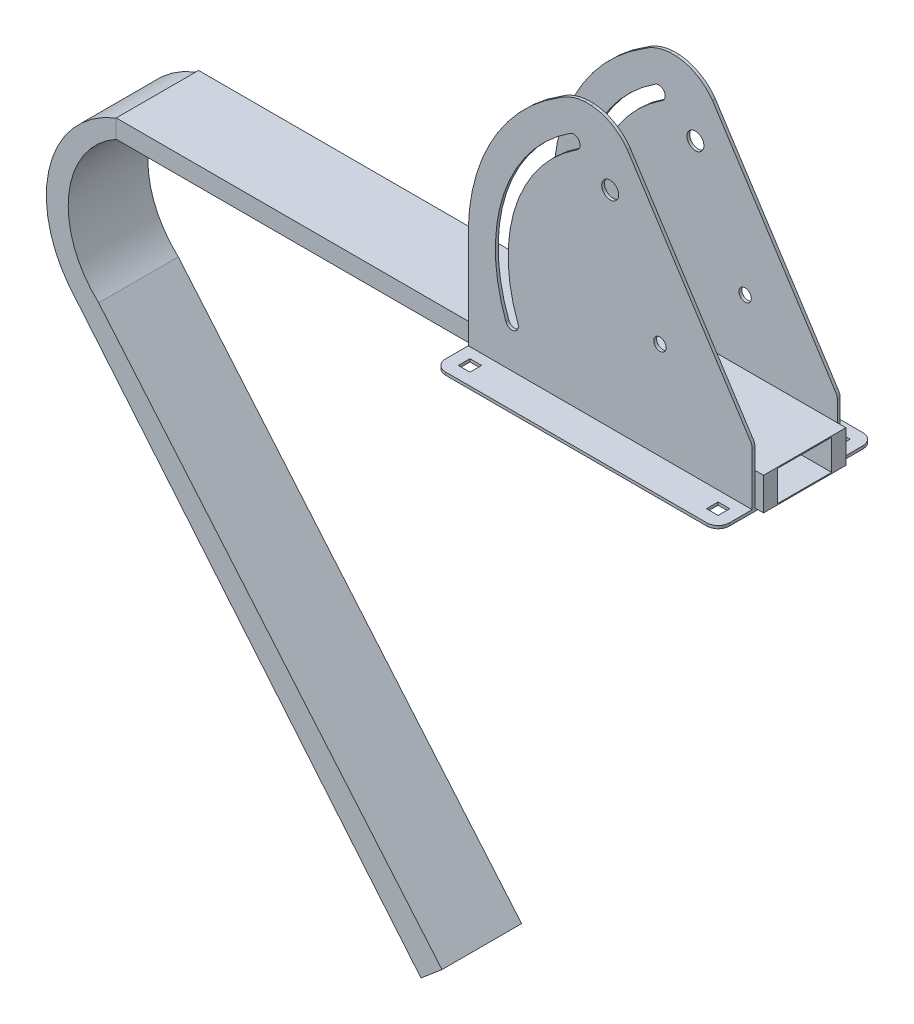
SolidWorks part; units mm, degrees
ref_plane "Alzado" through (0, 0, 0) normal (0, 0, 1) x (1, 0, 0)
ref_plane "Planta" through (0, 0, 0) normal (0, 1, 0) x (1, 0, 0)
ref_plane "Vista lateral" through (0, 0, 0) normal (1, 0, 0) x (0, 0, -1)
sketch "Croquis1" plane through (0, 0, 0) normal (0, 1, 0) x (1, 0, 0)
  line L0 (0, 46.5) -> (0, 38.3) construction
  line L1 (-100, 55) -> (100, 55)
  line L2 (-100, 55) -> (-100, -55)
  line L3 (-100, -55) -> (100, -55)
  line L4 (100, 55) -> (100, -55)
  line L5 (-100, 55) -> (100, -55) construction
  line L6 (-100, -55) -> (100, 55) construction
  line L7 (-91.5, 0) -> (-83.3, 0) construction
  line L8 (91.5, 0) -> (83.3, 0) construction
  line L9 (0, -46.5) -> (0, -38.3) construction
  line L11 (-91.5, 46.5) -> (91.5, 46.5)
  line L12 (-91.5, 46.5) -> (-91.5, -46.5)
  line L13 (-91.5, -46.5) -> (91.5, -46.5)
  line L14 (91.5, 46.5) -> (91.5, -46.5)
  line L15 (-83.3, 38.3) -> (83.3, 38.3)
  line L16 (-83.3, 38.3) -> (-83.3, -38.3)
  line L17 (-83.3, -38.3) -> (83.3, -38.3)
  line L18 (83.3, 38.3) -> (83.3, -38.3)
  line L19 (-91.5, 46.5) -> (-83.3, 46.5)
  line L20 (-91.5, 46.5) -> (-91.5, 38.3)
  line L21 (-91.5, 38.3) -> (-83.3, 38.3)
  line L22 (-83.3, 46.5) -> (-83.3, 38.3)
  line L23 (91.5, 46.5) -> (83.3, 46.5)
  line L24 (91.5, 46.5) -> (91.5, 38.3)
  line L25 (91.5, 38.3) -> (83.3, 38.3)
  line L26 (83.3, 46.5) -> (83.3, 38.3)
  line L27 (91.5, -46.5) -> (83.3, -46.5)
  line L28 (91.5, -46.5) -> (91.5, -38.3)
  line L29 (91.5, -38.3) -> (83.3, -38.3)
  line L30 (83.3, -46.5) -> (83.3, -38.3)
  line L31 (-91.5, -46.5) -> (-83.3, -46.5)
  line L32 (-91.5, -46.5) -> (-91.5, -38.3)
  line L33 (-91.5, -38.3) -> (-83.3, -38.3)
  line L34 (-83.3, -46.5) -> (-83.3, -38.3)
  point P0 (0, 0)
extrude "Saliente-Extruir1" add sketch "Croquis1" along normal blind 2 contours L4 L1 L2 L3 L11 L14 L13 L12 | L26 L11 L22 L15 | L18 L15 L16 L17 | L12 L33 L16 L21 | L34 L13 L30 L17 | L29 L14 L25 L18
sketch "Croquis2" plane through (0, 2, 0) normal (0, 1, 0) x (1, 0, 0)
  line L1 (-92, 55) -> (92, 55)
  line L2 (-100, 47) -> (-100, -47)
  line L3 (-92, -55) -> (92, -55)
  line L4 (100, 47) -> (100, -47)
  line L5 (-100, 55) -> (100, 55)
  line L6 (-100, 55) -> (-100, -55)
  line L7 (-100, -55) -> (100, -55)
  line L8 (100, 55) -> (100, -55)
  arc A0 (92, 55) -> (100, 47) centre (92, 47) cw
  arc A1 (92, -55) -> (100, -47) centre (92, -47) ccw
  arc A2 (-100, -47) -> (-92, -55) centre (-92, -47) ccw
  arc A3 (-92, 55) -> (-100, 47) centre (-92, 47) ccw
  point P10 (100, -55)
  point P15 (-100, 55)
  line M21 (100, -55) -> (100, 55)
  line M22 (100, 55) -> (-100, 55)
  line M23 (-100, 55) -> (-100, -55)
  line M24 (-100, -55) -> (100, -55)
  dimension "D1" = 8
extrude "Cortar-Extruir1" cut sketch "Croquis2" against normal blind 2 contours A3 M22 M23 | A2 M23 M24 | A1 M24 M21 | A0 M22 M21
sketch "Croquis3" plane through (0, 2, 0) normal (0, 1, 0) x (1, 0, 0)
  line L0 (0, 0) -> (0, 31) construction
  line L1 (0, 0) -> (0, -31) construction
  line L2 (0, 31) -> (100, 31) construction
  line L3 (100, 47) -> (100, -47) construction
  line L4 (100, 31) -> (100, 29) construction
  line L5 (0, -31) -> (-100, -31) construction
  line L6 (-100, 47) -> (-100, -47) construction
  line L7 (-100, -31) -> (-100, -29) construction
  line L9 (-100, -29) -> (100, -29)
  line L10 (-100, -29) -> (-100, -31)
  line L11 (-100, -31) -> (100, -31)
  line L12 (100, -29) -> (100, -31)
  line L13 (100, 29) -> (-100, 29)
  line L14 (100, 29) -> (100, 31)
  line L15 (100, 31) -> (-100, 31)
  line L16 (-100, 29) -> (-100, 31)
extrude "Saliente-Extruir2" add sketch "Croquis3" along normal blind 190
sketch "Croquis4" plane through (0, 0, 31) normal (0, 0, 1) x (1, 0, 0)
  line L0 (100, 2) -> (100, 39.1036) construction
  line L1 (100, 192) -> (100, 2) construction
  line L2 (-100, 2) -> (100, 2) construction
  line L3 (-100, 192) -> (-25.7532, 192) construction
  line L4 (-100, 192) -> (100, 192) construction
  line L5 (100, 42.0136) -> (35.0202, 42.0136) construction
  line L6 (35.0202, 2) -> (35.0202, 70.4936) construction
  line L7 (-92, 2) -> (92, 2) construction
  line L8 (-100.0233, 70.4936) -> (-80.4494, 70.4936) construction
  line L9 (-80.4494, 70.4936) -> (-72.1437, 70.4936) construction
  line L10 (98.1304, 44.2435) -> (12.0581, 177.6575)
  line L11 (-100, 2) -> (-100, 31.4973) construction
  line L12 (-100, 192) -> (-100, 2) construction
  line L13 (-100, 31.4973) -> (-73.6652, 31.4973) construction
  line L14 (-25.7532, 192) -> (-25.7532, 168.6761) construction
  line L15 (-25.7532, 168.6761) -> (-25.7532, 158.7584) construction
  line L16 (-73.6652, 31.4973) -> (-64.7965, 31.4973) construction
  line L17 (-81.3139, 2) -> (-100, 2)
  line L18 (-100, 192) -> (100, 192)
  line L19 (-100, 192) -> (-100, 2)
  line L20 (-100, 2) -> (100, 2)
  line L21 (100, 192) -> (100, 2)
  line L22 (-15.7046, 192) -> (-100, 192)
  circle A0 centre (35.0202, 70.4936) radius 4.35
  circle A2 centre (35.0202, 70.4936) radius 115.4696 construction
  circle A3 centre (35.0202, 70.4936) radius 107.1639 construction
  arc A4 (100, 39.1036) -> (98.1304, 44.2435) centre (92, 39.1036) ccw
  arc A5 (-69.2308, 31.4973) -> (-25.7532, 163.7173) centre (34.201, 70.7444) cw construction
  arc A6 (-28.192, 167.4991) -> (-73.4381, 29.9008) centre (34.201, 70.7444) ccw
  arc A7 (-23.3145, 159.9354) -> (-65.0236, 33.0937) centre (34.201, 70.7444) ccw
  arc A8 (-23.3145, 159.9354) -> (-28.192, 167.4991) centre (-25.7532, 163.7173) ccw
  arc A9 (-73.4381, 29.9008) -> (-65.0236, 33.0937) centre (-69.2308, 31.4973) ccw
  arc A10 (-35.9072, 185.4112) -> (12.0581, 177.6575) centre (-15.7046, 158.1509) cw
  arc A11 (-100.0233, 70.4936) -> (-35.9072, 185.4112) centre (35.0202, 70.4936) cw
  point P38 (-70.8908, 105.3014)
  line M19 (100, 192) -> (-100, 192)
  line M20 (-100, 192) -> (-100, 2)
  dimension "D1" = 8
extrude "Cortar-Extruir2" cut sketch "Croquis4" against normal blind 81 contours A11 A10 L22 M20 | A10 L10 A4 L21 M19 | A0 | A6 A9 A7 A8
sketch "Croquis5" plane through (0, 2, 0) normal (0, 1, 0) x (1, 0, 0)
  line L0 (100, 29) -> (106, 29)
  line L1 (100, 29) -> (-100, 29)
  line L2 (100, 29) -> (100, -29)
  line L3 (100, -29) -> (-100, -29)
  line L4 (-100, 29) -> (-100, -29)
  line L5 (106, 29) -> (106, -29)
  line L6 (106, -29) -> (100, -29)
  line L8 (106, 29) -> (100, 29)
  line L9 (106, 29) -> (106, -29)
  line L10 (106, -29) -> (100, -29)
  line L11 (100, 29) -> (100, -29)
  line L12 (-100, 29) -> (-350, 29)
  line L13 (-100, 29) -> (-100, -29)
  line L14 (-100, -29) -> (-350, -29)
  line L15 (-350, 29) -> (-350, -29)
  line M11 (100, -29) -> (100, 29)
  line M12 (100, 29) -> (-100, 29)
  line M13 (-100, 29) -> (-100, -29)
  line M14 (-100, -29) -> (100, -29)
extrude "Saliente-Extruir3" add sketch "Croquis5" along normal blind 13 contours L12 L15 L14 M13 | M14 M11 M12 M13 | L6 L5 L0 M11
sketch "Croquis6" plane through (0, 0, 29) normal (0, 0, 1) x (1, 0, 0)
  line L0 (-350, 2) -> (-289.0204, -102.3973) construction
  line L1 (-350, 2) -> (-451.8696, 2) construction
  line L2 (-451.8696, 2) -> (-109.856, -402.2691) construction
  line L3 (-135.2169, -402.2691) -> (-120.4355, -389.7639)
  line L4 (-383.1239, -103.8885) -> (-135.2169, -402.2691) construction
  line L6 (-109.856, -402.2691) -> (-362.2874, -103.8885)
  line L7 (-135.2169, -402.2691) -> (-383.1239, -103.8885)
  line L8 (-350, 2) -> (-350, 15)
  arc A0 (-350, 2) -> (-362.2874, -103.8885) centre (-318.1224, -55.3563) ccw
  arc A1 (-350, 15) -> (-383.1239, -103.8885) centre (-322.0356, -56.8498) ccw
  line M8 (-350, 15) -> (-350, 2)
extrude "Saliente-Extruir4" add sketch "Croquis6" along normal blind 0.1 and the other way blind 56 contours A1 L7 L3 L6 A0 M8
sketch "Croquis7" plane through (0, 0, -31) normal (0, 0, -1) x (-1, 0, 0)
  line L0 (-100, 2) -> (0, 2) construction
  line L1 (-100, 2) -> (100, 2) construction
  line L2 (0, 2) -> (0, 147) construction
  circle A0 centre (0, 147) radius 6
extrude "Cortar-Extruir3" cut sketch "Croquis7" against normal blind 80.1
sketch "Croquis10" plane through (0, 15, 0) normal (0, 1, 0) x (1, 0, 0)
  line L0 (100, -29) -> (-100, -29) construction
  line L1 (-43.1166, -29) -> (106, -29)
  line L2 (-43.1166, -29) -> (-43.1166, 29)
  line L3 (-43.1166, 29) -> (106, 29)
  line L4 (106, -29) -> (106, 29)
extrude "Saliente-Extruir5" add sketch "Croquis10" along normal blind 10
sketch "Croquis11" plane through (106, 0, 0) normal (1, 0, 0) x (0, 0, -1)
  line L0 (-29, 25) -> (29, 2) construction
  line L2 (-19, 2.75) -> (19, 2.75)
  line L3 (-19, 2.75) -> (-19, 24.25)
  line L4 (-19, 24.25) -> (19, 24.25)
  line L5 (19, 2.75) -> (19, 24.25)
  line L6 (-19, 2.75) -> (19, 24.25) construction
  line L7 (-19, 24.25) -> (19, 2.75) construction
  point P4 (0, 13.5)
extrude "Cortar-Extruir4" cut sketch "Croquis11" against normal blind 70
